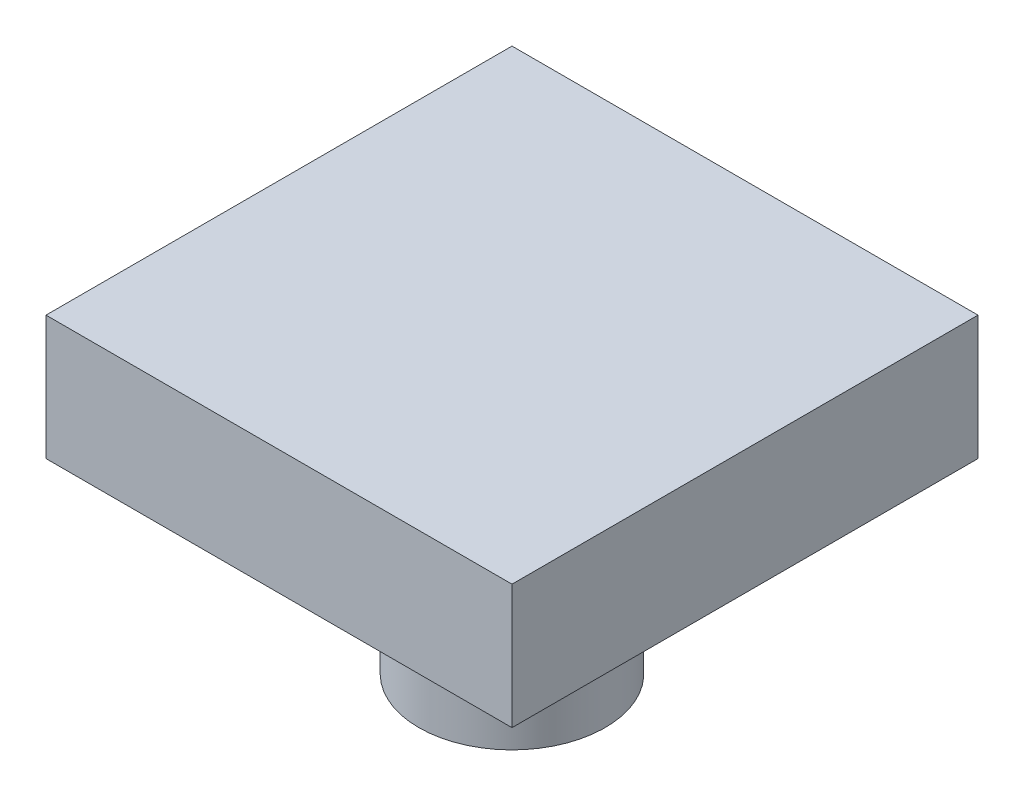
SolidWorks part; units mm, degrees
ref_plane "Front Plane" through (0, 0, 0) normal (0, 0, 1) x (1, 0, 0)
ref_plane "Top Plane" through (0, 0, 0) normal (0, 1, 0) x (1, 0, 0)
ref_plane "Right Plane" through (0, 0, 0) normal (1, 0, 0) x (0, 0, -1)
sketch "Sketch1" plane through (0, 0, 0) normal (0, 1, 0) x (1, 0, 0)
  line L0 (-15, -15) -> (15, -15)
  line L1 (15, -15) -> (15, 15)
  line L2 (15, 15) -> (-15, 15)
  line L3 (-15, 15) -> (-15, -15)
extrude "Boss-Extrude1" add sketch "Sketch1" along normal blind 8
sketch "Sketch2" plane through (0, 0, 0) normal (0, 1, 0) x (1, 0, 0)
  circle A0 centre (0, 0) radius 6
extrude "Boss-Extrude2" add sketch "Sketch2" against normal blind 12
